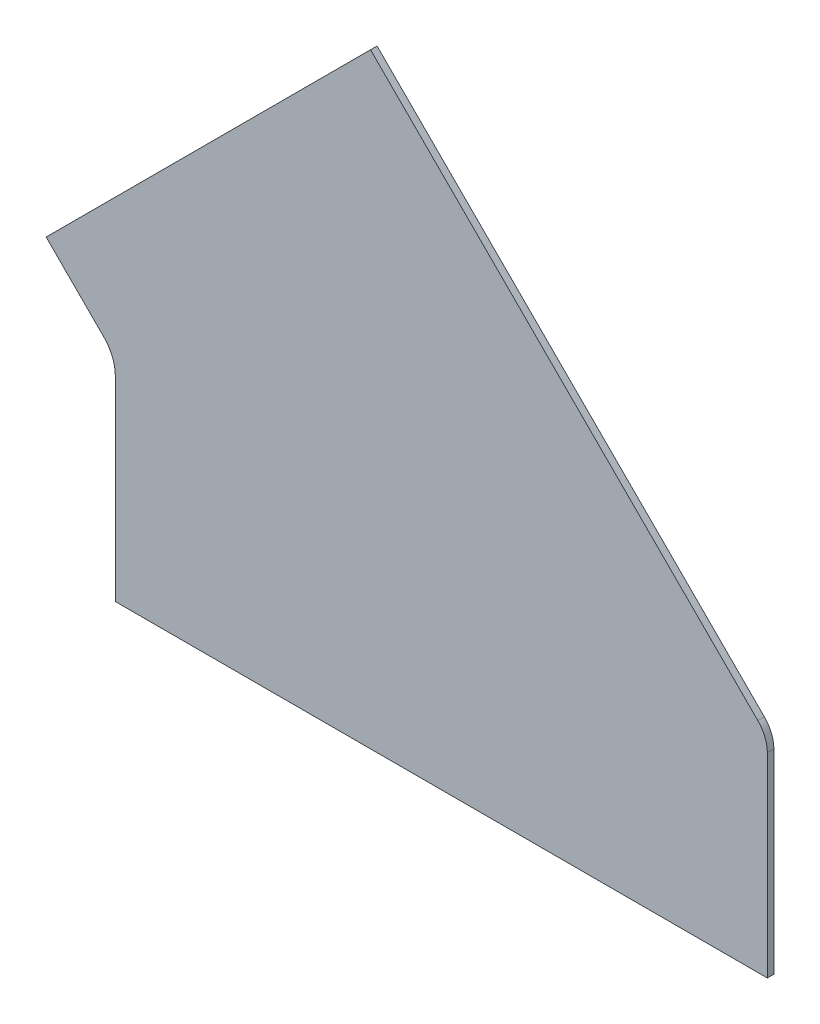
SolidWorks part; units mm, degrees
material "AISI 304"
ref_plane "Спереди" through (0, 0, 0) normal (0, 0, 1) x (1, 0, 0)
ref_plane "Сверху" through (0, 0, 0) normal (0, 1, 0) x (1, 0, 0)
ref_plane "Справа" through (0, 0, 0) normal (1, 0, 0) x (0, 0, -1)
sketch "Эскиз2" plane through (0, 0, 0) normal (0, 0, 1) x (1, 0, 0)
  line L5 (0, 0) -> (200, 0)
  line L6 (200, 0) -> (200, 64)
  line L8 (0, 65) -> (0, 0)
  line L9 (0, 65) -> (-21.2132, 86.2132)
  line L11 (78.2868, 185.7132) -> (200, 64)
  line L12 (-21.2132, 86.2132) -> (78.2868, 185.7132)
  dimension "D1" = 65
  dimension "D2" = 64
  dimension "D3" = 200
  dimension "D4" = 135
  dimension "D5" = 30
extrude "Бобышка-Вытянуть2" add sketch "Эскиз2" along normal blind 2
fillet "Скругление1" radius 10 1 edges at (200, 64, 1)
fillet "Скругление2" radius 12 1 edges at (0, 65, 1)
